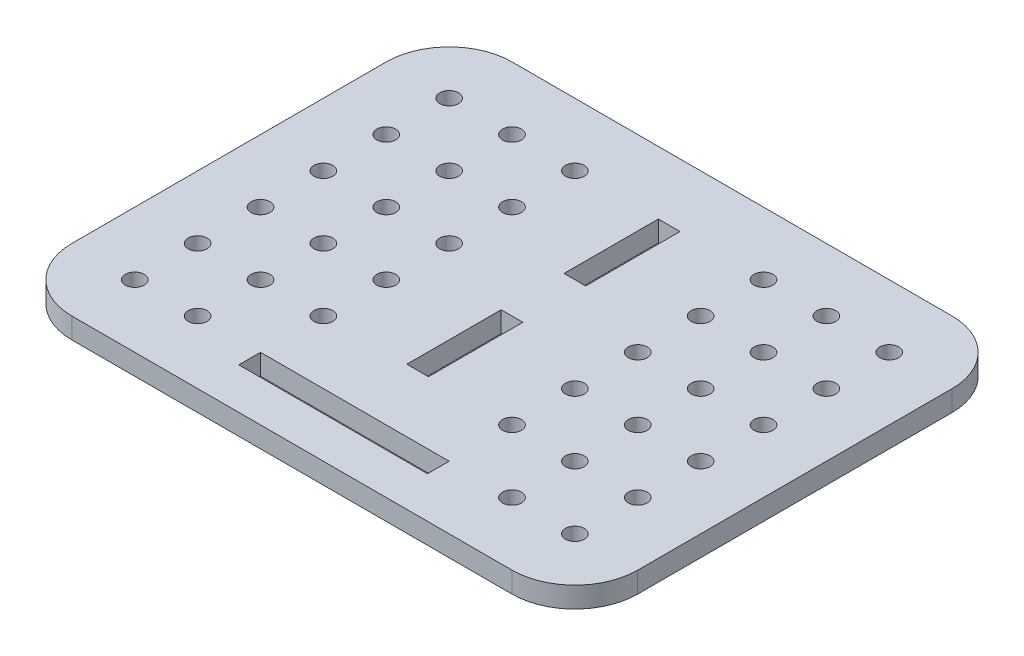
SolidWorks part; units mm, degrees
material "Pine"
ref_plane "Front Plane" through (0, 0, 0) normal (0, 0, 1) x (1, 0, 0)
ref_plane "Top Plane" through (0, 0, 0) normal (0, 1, 0) x (1, 0, 0)
ref_plane "Right Plane" through (0, 0, 0) normal (1, 0, 0) x (0, 0, -1)
sketch "Sketch1" plane through (0, 0, 0) normal (0, 1, 0) x (1, 0, 0)
  line L0 (0, 0) -> (0, -50000) construction
  line L1 (-35, 35) -> (35, 35)
  line L2 (-45, 25) -> (-45, -25)
  line L3 (-35, -35) -> (35, -35)
  line L4 (45, 25) -> (45, -25)
  line L5 (-45, 35) -> (45, -35) construction
  line L6 (-45, -35) -> (45, 35) construction
  line L7 (-1.725, -15) -> (1.725, -15)
  line L8 (1.725, -15) -> (1.725, 0)
  line L9 (1.725, 0) -> (-1.725, 0)
  line L10 (-1.725, 0) -> (-1.725, -15)
  line L11 (-1.725, 10) -> (1.725, 10)
  line L12 (1.725, 10) -> (1.725, 25)
  line L13 (1.725, 25) -> (-1.725, 25)
  line L14 (-1.725, 25) -> (-1.725, 10)
  line L15 (-35, -25) -> (-35, -15) construction
  line L16 (-35, -15) -> (-35, -5) construction
  line L17 (-35, -5) -> (-35, 5) construction
  line L18 (-35, 5) -> (-35, 15) construction
  line L19 (-35, 15) -> (-35, 25) construction
  line L20 (-35, 25) -> (-35, 35) construction
  line L21 (-35, 25) -> (-35, 35) construction
  line L22 (-35, 25) -> (-35, 35) construction
  line L25 (-25, -25) -> (-25, -15) construction
  line L26 (-25, -15) -> (-25, -5) construction
  line L27 (-25, -5) -> (-25, 5) construction
  line L28 (-25, 5) -> (-25, 15) construction
  line L29 (-25, 25) -> (-25, 15) construction
  line L30 (-25, 25) -> (-25, 35) construction
  line L32 (-15, -35) -> (-15, -25) construction
  line L34 (-15, -15) -> (-15, -5) construction
  line L35 (-15, -5) -> (-15, 5) construction
  line L36 (-15, 5) -> (-15, 15) construction
  line L37 (-15, 25) -> (-15, 15) construction
  line L38 (-15, 25) -> (-15, 35) construction
  line L39 (-15, -25) -> (15, -25)
  line L40 (15, -35) -> (15, -25) construction
  line L42 (15, -15) -> (15, -5) construction
  line L43 (15, -5) -> (15, 5) construction
  line L44 (15, 5) -> (15, 15) construction
  line L45 (15, 25) -> (15, 15) construction
  line L46 (15, 25) -> (15, 35) construction
  line L49 (25, -25) -> (25, -15) construction
  line L50 (25, -15) -> (25, -5) construction
  line L51 (25, -5) -> (25, 5) construction
  line L52 (25, 5) -> (25, 15) construction
  line L53 (25, 25) -> (25, 15) construction
  line L54 (25, 25) -> (25, 35) construction
  line L57 (35, -25) -> (35, -15) construction
  line L58 (35, -15) -> (35, -5) construction
  line L59 (35, -5) -> (35, 5) construction
  line L60 (35, 5) -> (35, 15) construction
  line L61 (35, 25) -> (35, 15) construction
  line L62 (35, 25) -> (35, 35) construction
  line L63 (-15, -25) -> (-15, -28.45)
  line L64 (-15, -28.45) -> (15, -28.45)
  line L65 (15, -25) -> (15, -28.45)
  line L66 (-15, -25) -> (15, -28.45) construction
  line L67 (-15, -28.45) -> (15, -25) construction
  arc A0 (-45, 25) -> (-35, 35) centre (-35, 25) cw
  arc A1 (35, 35) -> (45, 25) centre (35, 25) cw
  arc A2 (45, -25) -> (35, -35) centre (35, -25) cw
  arc A3 (-35, -35) -> (-45, -25) centre (-35, -25) cw
  circle A4 centre (-35, -25) radius 1.5
  circle A5 centre (-35, -15) radius 1.5
  circle A6 centre (-35, -5) radius 1.5
  circle A7 centre (-35, 5) radius 1.5
  circle A8 centre (-35, 15) radius 1.5
  circle A11 centre (-35, 25) radius 1.5
  circle A14 centre (-25, -25) radius 1.5
  circle A15 centre (-25, -15) radius 1.5
  circle A16 centre (-25, -5) radius 1.5
  circle A17 centre (-25, 5) radius 1.5
  circle A18 centre (-25, 15) radius 1.5
  circle A19 centre (-25, 25) radius 1.5
  circle A23 centre (-15, -15) radius 1.5
  circle A24 centre (-15, -5) radius 1.5
  circle A25 centre (-15, 5) radius 1.5
  circle A26 centre (-15, 15) radius 1.5
  circle A27 centre (-15, 25) radius 1.5
  circle A31 centre (15, -15) radius 1.5
  circle A32 centre (15, -5) radius 1.5
  circle A33 centre (15, 5) radius 1.5
  circle A34 centre (15, 15) radius 1.5
  circle A35 centre (15, 25) radius 1.5
  circle A38 centre (25, -25) radius 1.5
  circle A39 centre (25, -15) radius 1.5
  circle A40 centre (25, -5) radius 1.5
  circle A41 centre (25, 5) radius 1.5
  circle A42 centre (25, 15) radius 1.5
  circle A43 centre (25, 25) radius 1.5
  circle A46 centre (35, -25) radius 1.5
  circle A47 centre (35, -15) radius 1.5
  circle A48 centre (35, -5) radius 1.5
  circle A49 centre (35, 5) radius 1.5
  circle A50 centre (35, 15) radius 1.5
  circle A51 centre (35, 25) radius 1.5
  point P0 (0, 0)
  point P8 (0, -35)
  point P9 (0, 25)
  point P12 (0, -15)
  point P17 (0, 10)
  point P44 (0, 0)
  point P46 (0, 0)
  point P67 (0, -26.725)
  dimension "D7" = 10
  dimension "D8" = 3
  dimension "D1" = 70
  dimension "D2" = 90
  dimension "D3" = 15
  dimension "D4" = 3.45
  dimension "D5" = 10
  dimension "D6" = 20
  dimension "D9" = 10
  dimension "D10" = 10
  dimension "D11" = 10
  dimension "D12" = 30
  dimension "D13" = 10
  dimension "D14" = 10
  dimension "D15" = 3.45
  dimension "D16" = 30
  dimension "D17" = 10
extrude "Boss-Extrude1" add sketch "Sketch1" along normal blind 3.3
